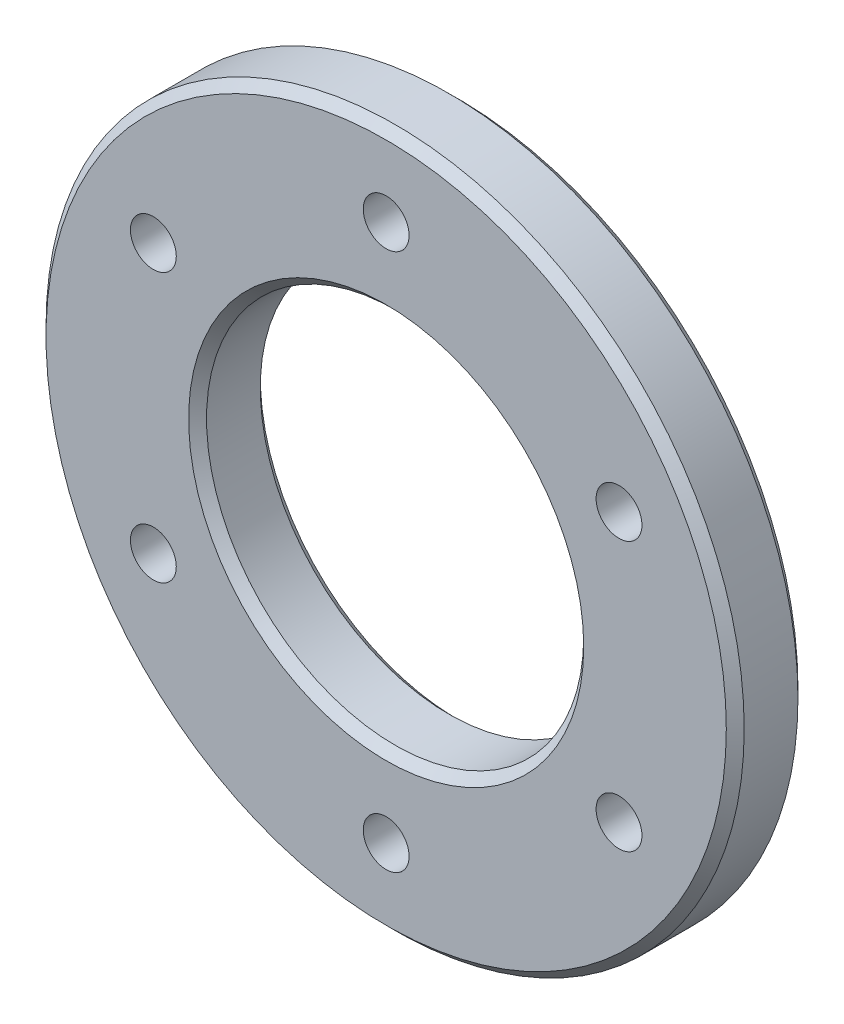
SolidWorks part; units mm, degrees
ref_plane "Front Plane" through (0, 0, 0) normal (0, 0, 1) x (1, 0, 0)
ref_plane "Top Plane" through (0, 0, 0) normal (0, 1, 0) x (1, 0, 0)
ref_plane "Right Plane" through (0, 0, 0) normal (1, 0, 0) x (0, 0, -1)
sketch "Sketch1" plane through (0, 0, 0) normal (0, 0, 1) x (1, 0, 0)
  circle A0 centre (0, 0) radius 30.9372
  circle A1 centre (0, 23.8252) radius 2.032
  circle A2 centre (0, 0) radius 16.7132
  circle A3 centre (20.6332, 11.9126) radius 2.032
  circle A4 centre (20.6332, -11.9126) radius 2.032
  circle A5 centre (0, -23.8252) radius 2.032
  circle A6 centre (-20.6332, -11.9126) radius 2.032
  circle A7 centre (-20.6332, 11.9126) radius 2.032
  point P19 (0, 0)
  dimension "D2" = 4.064
  dimension "D3" = 33.4264
  dimension "D4" = 61.8744
  dimension "D5" = 23.8252
  dimension "D1" = 6
extrude "Boss-Extrude1" add sketch "Sketch1" along normal blind 6.35
chamfer "Chamfer1" distance 0.7937 angle 45 4 edges at (30.9372, 0, 0) (16.7132, 0, 0) (16.7132, 0, 6.35) (30.9372, 0, 6.35)
